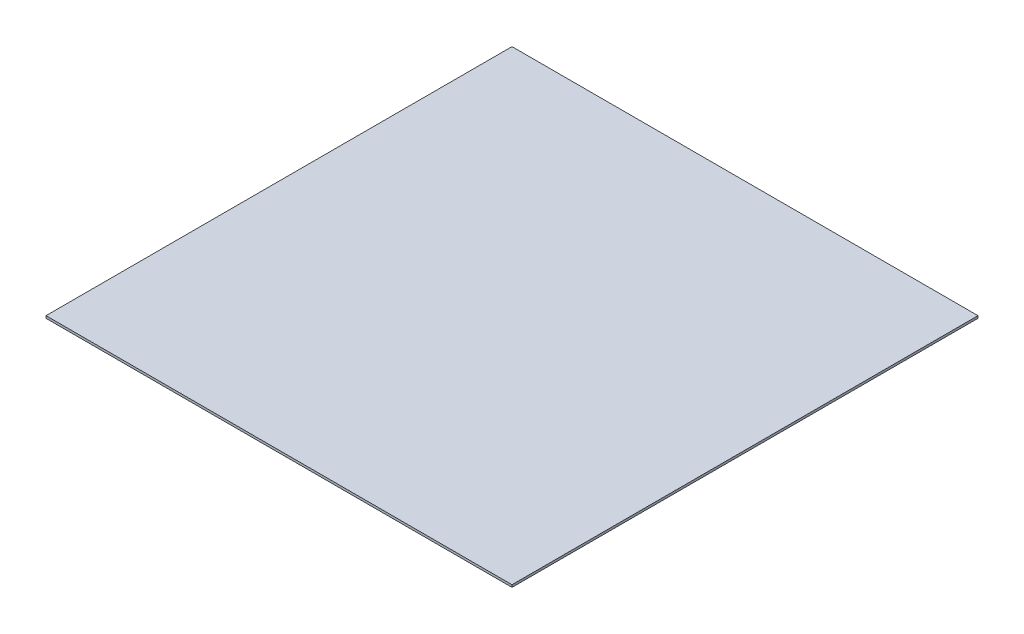
SolidWorks part; units mm, degrees
ref_plane "Front Plane" through (0, 0, 0) normal (0, 0, 1) x (1, 0, 0)
ref_plane "Top Plane" through (0, 0, 0) normal (0, 1, 0) x (1, 0, 0)
ref_plane "Right Plane" through (0, 0, 0) normal (1, 0, 0) x (0, 0, -1)
sketch "Sketch1" plane through (0, 0, 0) normal (0, 1, 0) x (1, 0, 0)
  line L1 (0, 0) -> (2540, 0)
  line L2 (0, 0) -> (0, 2540)
  line L3 (0, 2540) -> (2540, 2540)
  line L4 (2540, 0) -> (2540, 2540)
  dimension "D1" = 2540
  dimension "D2" = 2540
extrude "Boss-Extrude1" add sketch "Sketch1" along normal blind 12.7
